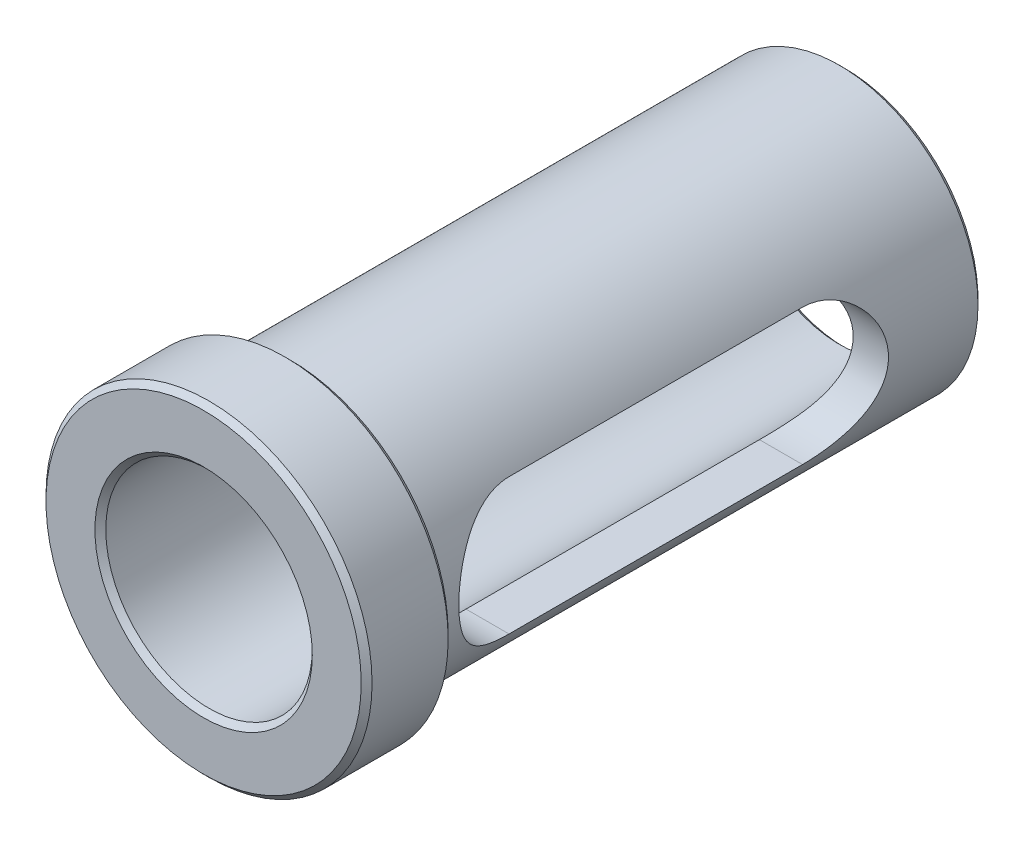
SolidWorks part; units mm, degrees
ref_plane "Piano frontale" through (0, 0, 0) normal (0, 0, 1) x (1, 0, 0)
ref_plane "Piano superiore" through (0, 0, 0) normal (0, 1, 0) x (1, 0, 0)
ref_plane "Piano destro" through (0, 0, 0) normal (1, 0, 0) x (0, 0, -1)
sketch "Schizzo1" plane through (0, 0, 0) normal (1, 0, 0) x (0, 0, -1)
  line L0 (0, 73.7793) -> (0, -73.7793) construction
  line L1 (-102.3813, 0) -> (102.3813, 0) construction
  line L2 (59, 30) -> (-59, 30)
  line L3 (-59, 30) -> (-59, -30)
  line L4 (59, 30) -> (59, -30)
  line L5 (59, -30) -> (-59, -30)
  point P4 (0, 0)
  point P8 (0, 0)
  point P12 (0, 30)
  point P14 (59, 0)
  point P15 (-59, 0)
  dimension "D1" = 118
  dimension "D2" = 60
extrude "Estrusione-Estrusione1" add sketch "Schizzo1" against normal blind 60
sketch "Schizzo2" plane through (0, 0, 0) normal (1, 0, 0) x (0, 0, -1)
  line L0 (-76.6108, 0) -> (80.6108, 0) construction
  line L1 (2, 38.8922) -> (2, -38.8922) construction
  line L2 (29, 12.534) -> (-25, 12.534)
  line L3 (29, -12.534) -> (-25, -12.534)
  line L4 (59, -30) -> (59, 30) construction
  line L5 (59, 30) -> (-59, 30) construction
  arc A0 (29, -12.534) -> (29, 12.534) centre (29, 0) ccw
  arc A1 (-25, -12.534) -> (-25, 12.534) centre (-25, 0) cw
  point P4 (2, 0)
  point P8 (2, 0)
  point P13 (2, -12.534)
  point P15 (2, 12.534)
  dimension "D2" = 12.534
  dimension "D1" = 54
  dimension "D3" = 30
  dimension "D4" = 30
extrude "Taglio-Estrusione1" cut sketch "Schizzo2" against normal blind 30
sketch "Schizzo3" plane through (0, 0, -59) normal (0, 0, -1) x (-1, 0, 0)
  line L1 (60, 30) -> (0, 30) construction
  line L2 (60, -30) -> (60, 30) construction
  line L3 (0, 30) -> (60, 30)
  line L4 (60, 30) -> (60, -30)
  line L5 (60, -30) -> (0, -30)
  line L6 (60, -30) -> (0, -30) construction
  line L7 (0, -30) -> (0, 30) construction
  line L8 (0, -30) -> (0, 30)
  circle A0 centre (30, 0) radius 25.5
  dimension "D3" = 51
  dimension "D1" = 30
  dimension "D2" = 30
extrude "Taglio-Estrusione4" cut sketch "Schizzo3" against normal blind 102
sketch "Schizzo4" plane through (0, 0, 59) normal (0, 0, 1) x (1, 0, 0)
  line L0 (0, 30) -> (0, -30) construction
  line L1 (-60, 30) -> (0, 30) construction
  line L2 (-60, 30) -> (0, 30)
  line L3 (0, 30) -> (0, -30)
  line L4 (0, -30) -> (-60, -30)
  line L5 (-60, -30) -> (-60, 30)
  circle A0 centre (-30, 0) radius 30
  line M1 (0, -30) -> (0, 30)
  line M2 (0, 30) -> (-60, 30)
  line M3 (-60, 30) -> (-60, -30)
  line M4 (-60, -30) -> (0, -30)
  dimension "D1" = 30
  dimension "D3" = 60
  dimension "D2" = 30
extrude "Taglio-Estrusione5" cut sketch "Schizzo4" against normal blind 18 contours A0 L2 M3 | A0 L3 M2 | A0 L4 M1 | A0 L5 M4
sketch "Schizzo5" plane through (0, 0, -59) normal (0, 0, -1) x (-1, 0, 0)
  circle A0 centre (30, 0) radius 19
  circle A1 centre (30, 0) radius 25.5 construction
extrude "Taglio-Estrusione6" cut sketch "Schizzo5" against normal through all
chamfer "Smusso1" distance 1 angle 45 1 edges at (-49, 0, -59)
chamfer "Smusso2" distance 1 angle 45 1 edges at (-55.5, 0, -59)
chamfer "Smusso3" distance 1 angle 45 1 edges at (0, 0, 43)
chamfer "Smusso4" distance 1 angle 45 1 edges at (-49, 0, 59)
chamfer "Smusso5" distance 1 angle 45 1 edges at (0, 0, 59)
